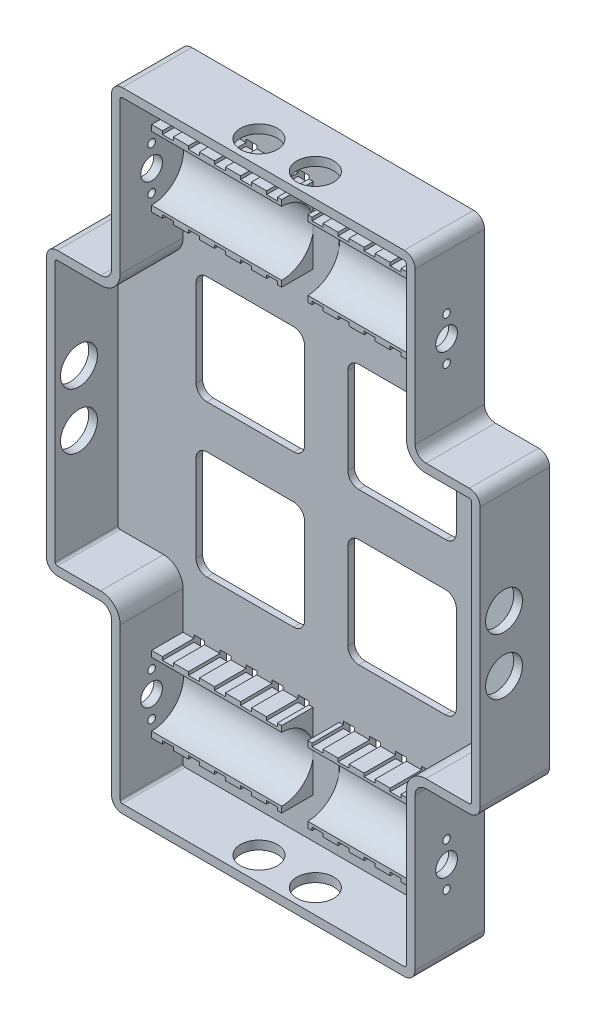
SolidWorks part; units mm, degrees
ref_plane "Front Plane" through (0, 0, 0) normal (0, 0, 1) x (1, 0, 0)
ref_plane "Top Plane" through (0, 0, 0) normal (0, 1, 0) x (1, 0, 0)
ref_plane "Right Plane" through (0, 0, 0) normal (1, 0, 0) x (0, 0, -1)
sketch "Sketch1" plane through (0, 0, 0) normal (0, 0, 1) x (1, 0, 0)
  line L0 (-70, -145) -> (70, -145)
  line L1 (70, -145) -> (70, -65)
  line L2 (70, -65) -> (100, -65)
  line L3 (100, -65) -> (100, 65)
  line L4 (100, 65) -> (70, 65)
  line L5 (70, 65) -> (70, 145)
  line L6 (70, 145) -> (-70, 145)
  line L7 (-70, 145) -> (-70, 65)
  line L8 (-70, 65) -> (-100, 65)
  line L9 (-100, 65) -> (-100, -65)
  line L10 (-100, -65) -> (-70, -65)
  line L11 (-70, -65) -> (-70, -145)
  line L12 (-70, 65) -> (70, 65) construction
  line L13 (70, 65) -> (70, -65) construction
  line L14 (70, -65) -> (-70, -65) construction
  line L15 (-70, -65) -> (-70, 65) construction
  line L16 (0, 65) -> (0, -65) construction
  dimension "D1" = 200
  dimension "D2" = 290
  dimension "D3" = 80
  dimension "D4" = 140
extrude "Boss-Extrude1" add sketch "Sketch1" along normal blind 3
fillet "Fillet1" radius 5 12 edges at (-70, -65, 1.5) (-100, -65, 1.5) (-70, 145, 1.5) (70, 145, 1.5) (70, 65, 1.5) (100, 65, 1.5) (100, -65, 1.5) (70, -65, 1.5) (70, -145, 1.5) (-70, -145, 1.5) (-70, 65, 1.5) (-100, 65, 1.5)
sketch "Sketch2" plane through (0, 0, 3) normal (0, 0, 1) x (1, 0, 0)
  line L0 (-96, 60) -> (-96, -60)
  line L1 (-95, -61) -> (-75, -61)
  line L2 (-66, -70) -> (-66, -140)
  line L3 (-65, -141) -> (65, -141)
  line L4 (66, -140) -> (66, -70)
  line L5 (75, -61) -> (95, -61)
  line L6 (96, -60) -> (96, 60)
  line L7 (95, 61) -> (75, 61)
  line L8 (66, 70) -> (66, 140)
  line L9 (65, 141) -> (-65, 141)
  line L10 (-66, 140) -> (-66, 70)
  line L11 (-75, 61) -> (-95, 61)
  line L12 (-100, 60) -> (-100, -60)
  line L13 (-95, -65) -> (-75, -65)
  line L14 (-70, -70) -> (-70, -140)
  line L15 (-65, -145) -> (65, -145)
  line L16 (70, -140) -> (70, -70)
  line L17 (75, -65) -> (95, -65)
  line L18 (100, -60) -> (100, 60)
  line L19 (95, 65) -> (75, 65)
  line L20 (70, 70) -> (70, 140)
  line L21 (65, 145) -> (-65, 145)
  line L22 (-70, 140) -> (-70, 70)
  line L23 (-75, 65) -> (-95, 65)
  line L24 (-100, 60) -> (-100, -60)
  line L25 (-95, -65) -> (-75, -65)
  line L26 (-70, -70) -> (-70, -140)
  line L27 (-65, -145) -> (65, -145)
  line L28 (70, -140) -> (70, -70)
  line L29 (75, -65) -> (95, -65)
  line L30 (100, -60) -> (100, 60)
  line L31 (95, 65) -> (75, 65)
  line L32 (70, 70) -> (70, 140)
  line L33 (65, 145) -> (-65, 145)
  line L34 (-70, 140) -> (-70, 70)
  line L35 (-75, 65) -> (-95, 65)
  arc A0 (-96, -60) -> (-95, -61) centre (-95, -60) ccw
  arc A1 (-66, -70) -> (-75, -61) centre (-75, -70) ccw
  arc A2 (-66, -140) -> (-65, -141) centre (-65, -140) ccw
  arc A3 (65, -141) -> (66, -140) centre (65, -140) ccw
  arc A4 (75, -61) -> (66, -70) centre (75, -70) ccw
  arc A5 (95, -61) -> (96, -60) centre (95, -60) ccw
  arc A6 (96, 60) -> (95, 61) centre (95, 60) ccw
  arc A7 (66, 70) -> (75, 61) centre (75, 70) ccw
  arc A8 (66, 140) -> (65, 141) centre (65, 140) ccw
  arc A9 (-65, 141) -> (-66, 140) centre (-65, 140) ccw
  arc A10 (-75, 61) -> (-66, 70) centre (-75, 70) ccw
  arc A11 (-95, 61) -> (-96, 60) centre (-95, 60) ccw
  arc A12 (-100, -60) -> (-95, -65) centre (-95, -60) ccw
  arc A13 (-70, -70) -> (-75, -65) centre (-75, -70) ccw
  arc A14 (-70, -140) -> (-65, -145) centre (-65, -140) ccw
  arc A15 (65, -145) -> (70, -140) centre (65, -140) ccw
  arc A16 (75, -65) -> (70, -70) centre (75, -70) ccw
  arc A17 (95, -65) -> (100, -60) centre (95, -60) ccw
  arc A18 (100, 60) -> (95, 65) centre (95, 60) ccw
  arc A19 (70, 70) -> (75, 65) centre (75, 70) ccw
  arc A20 (70, 140) -> (65, 145) centre (65, 140) ccw
  arc A21 (-65, 145) -> (-70, 140) centre (-65, 140) ccw
  arc A22 (-75, 65) -> (-70, 70) centre (-75, 70) ccw
  arc A23 (-95, 65) -> (-100, 60) centre (-95, 60) ccw
  arc A24 (-100, -60) -> (-95, -65) centre (-95, -60) ccw
  arc A25 (-70, -70) -> (-75, -65) centre (-75, -70) ccw
  arc A26 (-70, -140) -> (-65, -145) centre (-65, -140) ccw
  arc A27 (65, -145) -> (70, -140) centre (65, -140) ccw
  arc A28 (75, -65) -> (70, -70) centre (75, -70) ccw
  arc A29 (95, -65) -> (100, -60) centre (95, -60) ccw
  arc A30 (100, 60) -> (95, 65) centre (95, 60) ccw
  arc A31 (70, 70) -> (75, 65) centre (75, 70) ccw
  arc A32 (70, 140) -> (65, 145) centre (65, 140) ccw
  arc A33 (-65, 145) -> (-70, 140) centre (-65, 140) ccw
  arc A34 (-75, 65) -> (-70, 70) centre (-75, 70) ccw
  arc A35 (-95, 65) -> (-100, 60) centre (-95, 60) ccw
  dimension "D1" = 0
  dimension "D2" = 4
extrude "Boss-Extrude2" add sketch "Sketch2" along normal blind 29
sketch "Sketch3" plane through (-70, 0, 0) normal (-1, 0, 0) x (0, 0, 1)
  line L0 (0, -105) -> (17.5, -105) construction
  line L1 (0, -70) -> (0, -140) construction
  line L2 (17.5, -95) -> (17.5, -115) construction
  circle A0 centre (17.5, -105) radius 5
  circle A1 centre (17.5, -95) radius 1.75
  circle A2 centre (17.5, -115) radius 1.75
  dimension "D1" = 3.5
  dimension "D3" = 10
  dimension "D2" = 20
  dimension "D4" = 17.5
extrude "Cut-Extrude1" cut sketch "Sketch3" against normal blind 29
sketch "Sketch4" plane through (0, 0, 3) normal (0, 0, 1) x (1, 0, 0)
  line L0 (-66, -70) -> (-66, -140) construction
  line L1 (-66, -87.5) -> (-6, -87.5)
  line L2 (-66, -87.5) -> (-66, -122.5)
  line L3 (-66, -122.5) -> (-6, -122.5)
  line L4 (-6, -87.5) -> (-6, -122.5)
  line L5 (-66, -105) -> (-70, -105) construction
  line L6 (-70, -70) -> (-70, -140) construction
  dimension "D1" = 35
  dimension "D2" = 60
extrude "Boss-Extrude3" add sketch "Sketch4" along normal blind 14.5
sketch "Sketch5" plane through (-6, 0, 0) normal (1, 0, 0) x (0, 0, -1)
  line L0 (-17.5, -122.5) -> (-17.5, -87.5) construction
  circle A0 centre (-17.5, -105) radius 14.75
  dimension "D1" = 29.5
extrude "Cut-Extrude2" cut sketch "Sketch5" against normal blind 60
sketch "Sketch7" plane through (0, 0, 17.5) normal (0, 0, 1) x (1, 0, 0)
  line L0 (-61, -89) -> (-61, -121) construction
  line L1 (-61, -121) -> (-56, -121)
  line L2 (-61, -121) -> (-61, -124)
  line L3 (-61, -124) -> (-56, -124)
  line L4 (-56, -121) -> (-56, -124)
  line L5 (-61, -89) -> (-56, -89)
  line L6 (-61, -89) -> (-61, -86)
  line L7 (-61, -86) -> (-56, -86)
  line L8 (-56, -89) -> (-56, -86)
  line L9 (-56, -121) -> (-56, -89) construction
  line L10 (-61, -105) -> (-66, -105) construction
  line L11 (-66, -70) -> (-66, -140) construction
  dimension "D1" = 5
  dimension "D2" = 32
  dimension "D3" = 3
  dimension "D4" = 5
extrude "Cut-Extrude3" cut sketch "Sketch7" against normal through all
sketch "Sketch8" plane through (-61, 0, 0) normal (1, 0, 0) x (0, 0, -1)
  line L0 (0, -89) -> (0, -121)
  line L1 (0, -121) -> (-3, -121)
  line L2 (-3, -121) -> (-3, -89) construction
  line L3 (0, -89) -> (-17.5, -89) construction
  line L4 (-3, -89) -> (0, -89)
  line L5 (-3, -89) -> (-1.5, -90.5)
  line L6 (-1.5, -90.5) -> (-1.5, -119.5)
  line L7 (-1.5, -119.5) -> (-3, -121)
  line L8 (-1.5, -105) -> (0, -105) construction
  dimension "D1" = 1.5
  dimension "D2" = 3
  dimension "D3" = 1.5
extrude "Cut-Extrude4" cut sketch "Sketch8" along normal blind 5
pattern_linear "LPattern1" count 5 spacing 12 along (1, 0, 0) of "Cut-Extrude3", "Cut-Extrude4"
mirror "Mirror1" about plane through (0, 0, 0) normal (1, 0, 0) of "LPattern1", "Cut-Extrude4", "Cut-Extrude3", "Cut-Extrude1", "Boss-Extrude3", "Cut-Extrude2" second plane through (0, 0, 0) second plane normal (0, 1, 0)
sketch "Sketch9" plane through (0, 0, 3) normal (0, 0, 1) x (1, 0, 0)
  line L0 (-60, -40) -> (-40, -40)
  line L1 (-65, 40) -> (65, 40) construction
  line L2 (-65, 40) -> (-65, -40) construction
  line L3 (-65, -40) -> (65, -40) construction
  line L4 (65, 40) -> (65, -40) construction
  line L5 (-65, 40) -> (65, -40) construction
  line L6 (-65, -40) -> (65, 40) construction
  line L7 (-35, -65) -> (35, -65) construction
  line L8 (-35, -65) -> (-35, 65) construction
  line L9 (-35, 65) -> (35, 65) construction
  line L10 (35, -65) -> (35, 65) construction
  line L11 (-35, -65) -> (35, 65) construction
  line L12 (-35, 65) -> (35, -65) construction
  line L13 (-35, -45) -> (-35, -60)
  line L14 (-30, -65) -> (30, -65)
  line L15 (35, -60) -> (35, -45)
  line L16 (40, -40) -> (60, -40)
  line L17 (65, -35) -> (65, 35)
  line L18 (60, 40) -> (40, 40)
  line L19 (35, 45) -> (35, 60)
  line L20 (30, 65) -> (-30, 65)
  line L21 (-35, 60) -> (-35, 45)
  line L22 (-40, 40) -> (-60, 40)
  line L23 (-65, 35) -> (-65, -35)
  arc A0 (-60, -40) -> (-65, -35) centre (-60, -35) cw
  arc A1 (-40, -40) -> (-35, -45) centre (-40, -45) cw
  arc A2 (-35, -60) -> (-30, -65) centre (-30, -60) ccw
  arc A3 (30, -65) -> (35, -60) centre (30, -60) ccw
  arc A4 (35, -45) -> (40, -40) centre (40, -45) cw
  arc A5 (60, -40) -> (65, -35) centre (60, -35) ccw
  arc A6 (65, 35) -> (60, 40) centre (60, 35) ccw
  arc A7 (40, 40) -> (35, 45) centre (40, 45) cw
  arc A8 (35, 60) -> (30, 65) centre (30, 60) ccw
  arc A9 (-30, 65) -> (-35, 60) centre (-30, 60) ccw
  arc A10 (-35, 45) -> (-40, 40) centre (-40, 45) cw
  arc A11 (-60, 40) -> (-65, 35) centre (-60, 35) ccw
  point P0 (0, 0)
  point P6 (0, 0)
  point P20 (-35, -40)
  point P29 (35, -40)
  point P38 (35, 40)
  point P47 (-35, 40)
  dimension "D5" = 5
  dimension "D1" = 80
  dimension "D2" = 70
  dimension "D3" = 130
  dimension "D4" = 130
sketch "Sketch11" plane through (0, 145, 0) normal (0, 1, 0) x (1, 0, 0)
  line L0 (-13, -21) -> (13, -21) construction
  line L1 (0, -21) -> (0, 0) construction
  line L2 (65, -32) -> (-65, -32) construction
  circle A0 centre (-13, -21) radius 8.5
  circle A1 centre (13, -21) radius 8.5
  dimension "D1" = 17
  dimension "D2" = 26
  dimension "D3" = 11
extrude "Cut-Extrude6" cut sketch "Sketch11" against normal up to next
mirror "Mirror2" about plane through (0, 0, 0) normal (0, 1, 0) of "Cut-Extrude6"
sketch "Sketch12" plane through (100, 0, 0) normal (1, 0, 0) x (0, 0, -1)
  line L0 (-21, 13) -> (-21, -13) construction
  line L1 (-21, 0) -> (0, 0) construction
  line L2 (-32, -60) -> (-32, 60) construction
  circle A0 centre (-21, 13) radius 8.5
  circle A1 centre (-21, -13) radius 8.5
  dimension "D1" = 17
  dimension "D2" = 26
  dimension "D3" = 11
extrude "Cut-Extrude7" cut sketch "Sketch12" against normal through all
sketch "Sketch13" plane through (0, 0, 0) normal (0, 0, -1) x (-1, 0, 0)
  line L1 (-55, 60) -> (-15, 60)
  line L2 (-60, 55) -> (-60, 15)
  line L3 (-55, 10) -> (-15, 10)
  line L4 (-10, 55) -> (-10, 15)
  line L5 (-60, 60) -> (-10, 10) construction
  line L6 (-60, 10) -> (-10, 60) construction
  arc A0 (-60, 15) -> (-55, 10) centre (-55, 15) ccw
  arc A1 (-15, 10) -> (-10, 15) centre (-15, 15) ccw
  arc A2 (-15, 60) -> (-10, 55) centre (-15, 55) cw
  arc A3 (-55, 60) -> (-60, 55) centre (-55, 55) ccw
  point P0 (-35, 35)
  dimension "D5" = 5
  dimension "D1" = 10
  dimension "D2" = 10
  dimension "D3" = 50
  dimension "D4" = 50
extrude "Cut-Extrude8" cut sketch "Sketch13" against normal through all
mirror "Mirror3" about plane through (0, 0, 0) normal (1, 0, 0) of "Cut-Extrude8" second plane through (0, 0, 0) second plane normal (0, 1, 0)
